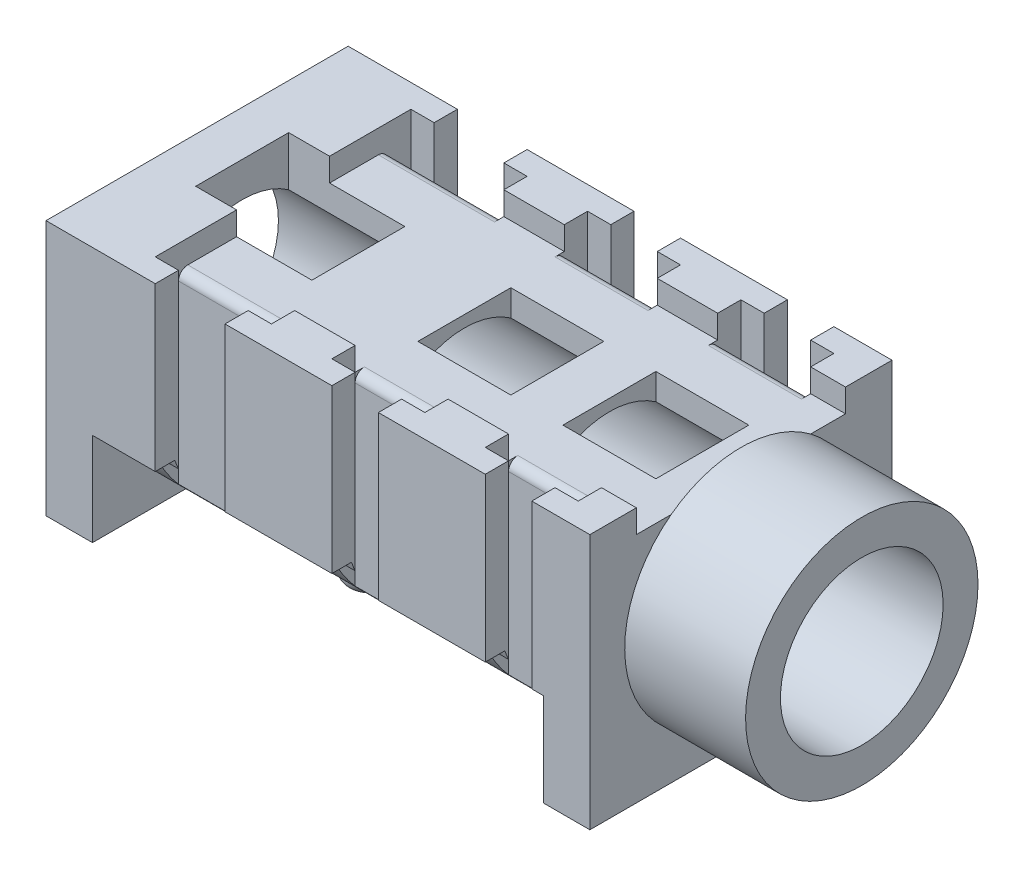
SolidWorks part; units mm, degrees
ref_plane "Front Plane" through (0, 0, 0) normal (0, 0, 1) x (1, 0, 0)
ref_plane "Top Plane" through (0, 0, 0) normal (0, 1, 0) x (1, 0, 0)
ref_plane "Right Plane" through (0, 0, 0) normal (1, 0, 0) x (0, 0, -1)
sketch "Sketch1" plane through (0, 0, 0) normal (0, 1, 0) x (1, 0, 0)
  line L1 (-5.85, -3.25) -> (5.85, -3.25)
  line L2 (-5.85, -3.25) -> (-5.85, 3.25)
  line L3 (-5.85, 3.25) -> (5.85, 3.25)
  line L4 (5.85, -3.25) -> (5.85, 3.25)
  line L5 (-5.85, -3.25) -> (5.85, 3.25) construction
  line L6 (-5.85, 3.25) -> (5.85, -3.25) construction
  point P0 (0, 0)
  dimension "D1" = 11.7
  dimension "D2" = 6.5
extrude "Boss-Extrude1" add sketch "Sketch1" along normal blind 5.5
sketch "Sketch2" plane through (5.85, 0, 0) normal (1, 0, 0) x (0, 0, -1)
  line L0 (-3.25, 5.5) -> (3.25, 5.5) construction
  circle A0 centre (0, 3) radius 1.75
  dimension "D1" = 3.5
  dimension "D2" = 2.5
extrude "Cut-Extrude1" cut sketch "Sketch2" against normal blind 15.5
sketch "Sketch3" plane through (5.85, 0, 0) normal (1, 0, 0) x (0, 0, -1)
  circle A0 centre (0, 3) radius 1.75
  circle A1 centre (0, 3) radius 2.5
  dimension "D1" = 5
extrude "Boss-Extrude2" add sketch "Sketch3" along normal blind 2.6
sketch "Sketch4" plane through (5.85, 0, 0) normal (1, 0, 0) x (0, 0, -1)
  line L0 (-4.687, 2) -> (-2.8284, 2)
  line L1 (-3.25, 0) -> (3.25, 0) construction
  line L2 (-4.687, 2) -> (-4.687, -1.4908)
  line L3 (-4.687, -1.4908) -> (5.3292, -1.4908)
  line L4 (5.3292, -1.4908) -> (5.3292, 2)
  line L5 (2.8284, 2) -> (5.3292, 2)
  arc A0 (-2.8284, 2) -> (2.8284, 2) centre (0, 3) ccw
  dimension "D1" = 2
extrude "Cut-Extrude2" cut sketch "Sketch4" against normal blind 9.7 from offset 1 offset against normal yes
sketch "Sketch5" plane through (0, 5.5, 0) normal (0, 1, 0) x (1, 0, 0)
  line L1 (5.85, 3.25) -> (-5.85, 3.25) construction
  line L2 (-3.5, 4.45) -> (-2, 4.45)
  line L3 (-3.5, 4.45) -> (-3.5, 2.75)
  line L4 (-7.3757, 0) -> (11.7586, 0) construction
  line L5 (-2, 4.45) -> (-2, 2.75)
  line L6 (-3.5, 4.45) -> (-2, 2.05) construction
  line L8 (-3.5, 2.05) -> (-2, 4.45) construction
  line L9 (-5.85, 3.25) -> (-5.85, -3.25) construction
  line L10 (0.3, 4.45) -> (1.3, 4.45)
  line L11 (0.3, 4.45) -> (0.3, 2.75)
  line L12 (3.6, -2.05) -> (4.6, -4.45) construction
  line L13 (1.3, 4.45) -> (1.3, 2.75)
  line L14 (0.3, 4.45) -> (1.3, 2.05) construction
  line L15 (0.3, 2.05) -> (1.3, 4.45) construction
  line L16 (3.6, 4.45) -> (4.6, 4.45)
  line L17 (3.6, 4.45) -> (3.6, 2.75)
  line L18 (3.6, -4.45) -> (4.6, -2.05) construction
  line L19 (4.6, 4.45) -> (4.6, 2.75)
  line L20 (3.6, 4.45) -> (4.6, 2.05) construction
  line L21 (3.6, 2.05) -> (4.6, 4.45) construction
  line L22 (4.6, 2.75) -> (5.1, 2.75)
  line L23 (-4, 2.25) -> (-1.5, 2.25)
  line L24 (-4, 2.25) -> (-4, 2.75)
  line L25 (-4, 2.75) -> (-3.5, 2.75)
  line L26 (-1.5, 2.25) -> (-1.5, 2.75)
  line L27 (-0.2, 2.25) -> (1.8, 2.25)
  line L28 (-0.2, 2.25) -> (-0.2, 2.75)
  line L29 (-0.2, 2.75) -> (0.3, 2.75)
  line L30 (1.8, 2.25) -> (1.8, 2.75)
  line L31 (3.1, 2.25) -> (5.1, 2.25)
  line L32 (3.1, 2.25) -> (3.1, 2.75)
  line L33 (3.1, 2.75) -> (3.6, 2.75)
  line L34 (5.1, 2.25) -> (5.1, 2.75)
  line L35 (-2, 2.75) -> (-1.5, 2.75)
  line L36 (1.3, 2.75) -> (1.8, 2.75)
  line L37 (0.3, -2.05) -> (1.3, -4.45) construction
  line L38 (0.3, -4.45) -> (1.3, -2.05) construction
  line L39 (-3.5, -2.05) -> (-2, -4.45) construction
  line L40 (-3.5, -4.45) -> (-2, -2.05) construction
  line L41 (1.3, -2.75) -> (1.8, -2.75)
  line L42 (-2, -2.75) -> (-1.5, -2.75)
  line L43 (5.1, -2.25) -> (5.1, -2.75)
  line L44 (3.1, -2.75) -> (3.6, -2.75)
  line L45 (3.1, -2.25) -> (3.1, -2.75)
  line L46 (3.1, -2.25) -> (5.1, -2.25)
  line L47 (1.8, -2.25) -> (1.8, -2.75)
  line L48 (-0.2, -2.75) -> (0.3, -2.75)
  line L49 (-0.2, -2.25) -> (-0.2, -2.75)
  line L50 (-0.2, -2.25) -> (1.8, -2.25)
  line L51 (-1.5, -2.25) -> (-1.5, -2.75)
  line L52 (-4, -2.75) -> (-3.5, -2.75)
  line L53 (-4, -2.25) -> (-4, -2.75)
  line L54 (-4, -2.25) -> (-1.5, -2.25)
  line L55 (4.6, -2.75) -> (5.1, -2.75)
  line L56 (4.6, -4.45) -> (4.6, -2.75)
  line L57 (3.6, -4.45) -> (3.6, -2.75)
  line L58 (3.6, -4.45) -> (4.6, -4.45)
  line L59 (1.3, -4.45) -> (1.3, -2.75)
  line L60 (0.3, -4.45) -> (0.3, -2.75)
  line L61 (0.3, -4.45) -> (1.3, -4.45)
  line L62 (-2, -4.45) -> (-2, -2.75)
  line L63 (-3.5, -4.45) -> (-3.5, -2.75)
  line L64 (-3.5, -4.45) -> (-2, -4.45)
  point P0 (-2.75, 3.25)
  point P7 (0.8, 3.25)
  point P12 (4.1, 3.25)
  point P70 (4.1, -3.25)
  point P71 (0.8, -3.25)
  point P72 (-2.75, -3.25)
  dimension "D1" = 3.1
  dimension "D2" = 6.65
  dimension "D3" = 9.95
  dimension "D4" = 1.5
  dimension "D5" = 1
  dimension "D6" = 1
  dimension "D7" = 1
  dimension "D8" = 2.4
  dimension "D9" = 2.4
  dimension "D10" = 0.5
  dimension "D11" = 2.5
  dimension "D12" = 1.25
  dimension "D13" = 2
  dimension "D14" = 2
  dimension "D15" = 1
  dimension "D16" = 1
  dimension "D17" = 1
  dimension "D18" = 1
extrude "Cut-Extrude3" cut sketch "Sketch5" against normal blind 10
sketch "Sketch6" plane through (0, 5.5, 0) normal (0, 1, 0) x (1, 0, 0)
  line L0 (-5.85, 0) -> (5.85, 0) construction
  line L1 (-5.85, 3.25) -> (-5.85, -3.25) construction
  line L3 (-4.88, -1) -> (-2.38, -1)
  line L4 (-4.88, -1) -> (-4.88, 1)
  line L5 (-4.88, 1) -> (-2.38, 1)
  line L6 (-2.38, -1) -> (-2.38, 1)
  line L7 (-4.88, -1) -> (-2.38, 1) construction
  line L8 (-4.88, 1) -> (-2.38, -1) construction
  line L9 (-0.1, -1) -> (1.9, -1)
  line L10 (-0.1, -1) -> (-0.1, 1)
  line L11 (-0.1, 1) -> (1.9, 1)
  line L12 (1.9, -1) -> (1.9, 1)
  line L13 (-0.1, -1) -> (1.9, 1) construction
  line L14 (-0.1, 1) -> (1.9, -1) construction
  line L15 (3.02, -1) -> (5.02, -1)
  line L16 (3.02, -1) -> (3.02, 1)
  line L17 (3.02, 1) -> (5.02, 1)
  line L18 (5.02, -1) -> (5.02, 1)
  line L19 (3.02, -1) -> (5.02, 1) construction
  line L20 (3.02, 1) -> (5.02, -1) construction
  point P5 (-3.63, 0)
  point P10 (0.9, 0)
  point P15 (4.02, 0)
  dimension "D1" = 0.97
  dimension "D2" = 2.5
  dimension "D3" = 2
  dimension "D4" = 5.75
  dimension "D5" = 2
  dimension "D6" = 2
  dimension "D7" = 2
  dimension "D8" = 2
  dimension "D9" = 8.87
extrude "Cut-Extrude4" cut sketch "Sketch6" against normal blind 2
sketch "Sketch7" plane through (0, 5.5, 0) normal (0, 1, 0) x (1, 0, 0)
  line L0 (5.85, 0) -> (5.85, 3.25) construction
  line L1 (5.85, 2.25) -> (-4, 2.25)
  line L2 (5.85, 2.25) -> (5.85, -2.25)
  line L3 (5.85, -2.25) -> (-4, -2.25)
  line L4 (-4, 2.25) -> (-4, -2.25)
  dimension "D1" = 0
extrude "Cut-Extrude5" cut sketch "Sketch7" against normal blind 0.5
fillet "Fillet1" radius 0.2 6 edges at (4.1, 5, 2.25) (0.8, 5, 2.25) (-2.75, 5, 2.25) (-2.75, 5, -2.25) (0.8, 5, -2.25) (4.1, 5, -2.25)
sketch "Sketch8" plane through (0, 0, 0) normal (0, -1, 0) x (1, 0, 0)
  line L0 (5.85, -2.5) -> (5.85, 2.5) construction
  circle A0 centre (4.05, 0) radius 0.5
  circle A1 centre (-2.15, 0) radius 0.5
  dimension "D1" = 1
  dimension "D3" = 6.2
  dimension "D2" = 1.8
extrude "Boss-Extrude3" add sketch "Sketch8" along normal blind 1 and the other way up to surface other way up to face at (-0.0957, 1.5353, 0)
fillet "Fillet2" radius 0.3 2 edges at (4.05, -1, -0.5) (-2.15, -1, -0.5)
